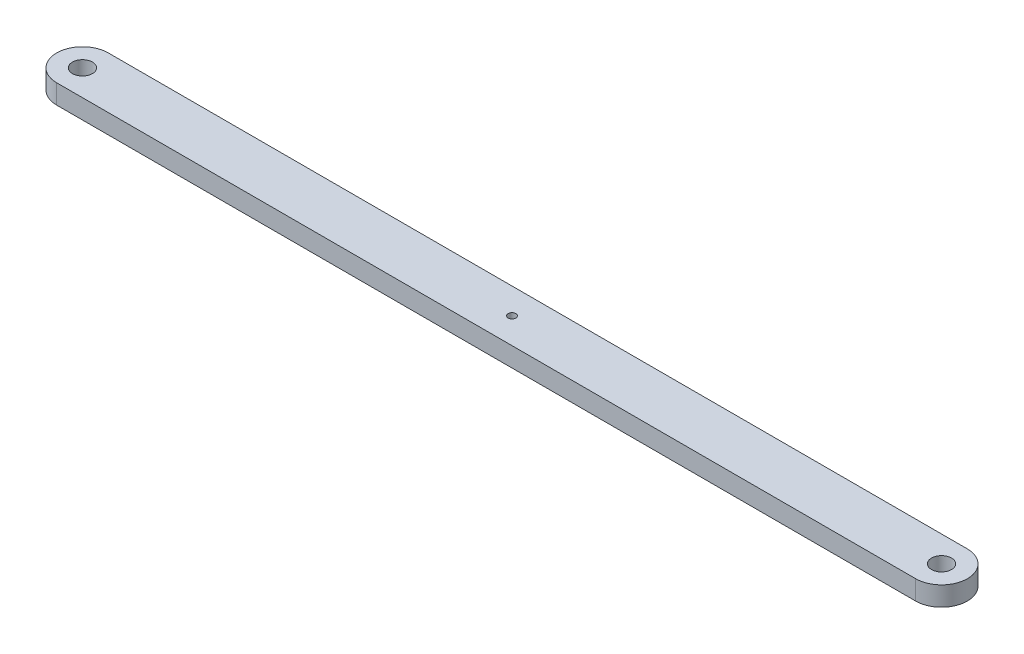
SolidWorks part; units mm, degrees
material "3mm Birch Ply Wood"
ref_plane "Front Plane" through (0, 0, 0) normal (0, 0, 1) x (1, 0, 0)
ref_plane "Top Plane" through (0, 0, 0) normal (0, 1, 0) x (1, 0, 0)
ref_plane "Right Plane" through (0, 0, 0) normal (1, 0, 0) x (0, 0, -1)
sketch "Sketch1" plane through (0, 0, 0) normal (0, 1, 0) x (1, 0, 0)
  line L0 (66.5, 0) -> (-66.5, 0) construction
  line L1 (0, 0) -> (0, 37.6997) construction
  line L2 (-66.5, 4) -> (66.5, 4)
  line L4 (66.5, -4) -> (-66.5, -4)
  circle A0 centre (-66.5, 0) radius 1.55
  arc A1 (-66.5, 4) -> (-66.5, -4) centre (-66.5, 0) ccw
  arc A2 (66.5, 4) -> (66.5, -4) centre (66.5, 0) cw
  circle A3 centre (66.5, 0) radius 1.55
  point P9 (0, 4)
  point P10 (0, 0)
  point P14 (0, -4)
extrude "Boss-Extrude1" add sketch "Sketch1" along normal blind 3
sketch "Sketch2" plane through (0, 0, 0) normal (0, 1, 0) x (1, 0, 0)
  line L0 (0, 4) -> (0, 0) construction
  line L1 (66.5, 4) -> (-66.5, 4) construction
  circle A0 centre (0, 0) radius 0.6
extrude "Cut-Extrude2" cut sketch "Sketch2" against normal through all and the other way through all
